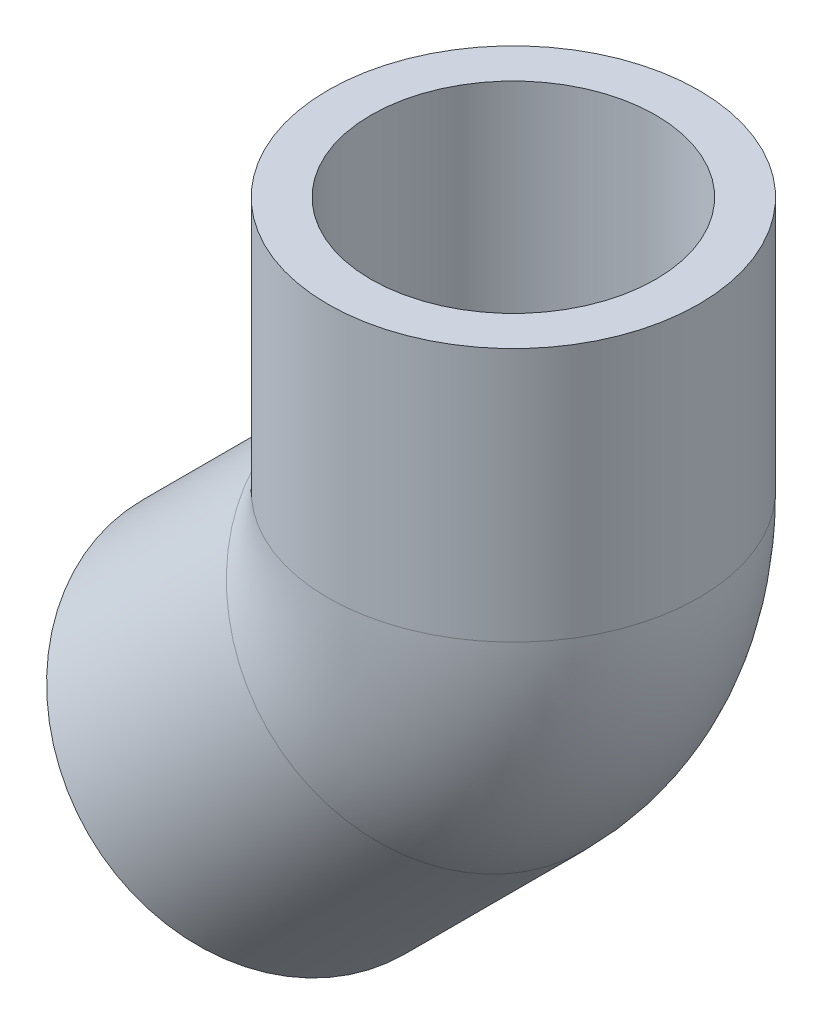
SolidWorks part; units mm, degrees
ref_plane "Front Plane" through (0, 0, 0) normal (0, 0, 1) x (1, 0, 0)
ref_plane "Top Plane" through (0, 0, 0) normal (0, 1, 0) x (1, 0, 0)
ref_plane "Right Plane" through (0, 0, 0) normal (1, 0, 0) x (0, 0, -1)
sketch "Sketch1" plane through (0, 0, 0) normal (0, 0, 1) x (1, 0, 0)
  line L0 (0, 0) -> (0, 25.4) construction
  line L1 (0, 0) -> (-17.9605, -17.9605) construction
  line L2 (-8.1361, -27.7849) -> (-27.7849, -8.1361) construction
  line L3 (10.668, 6.35) -> (-10.668, 6.35) construction
  line L4 (-13.8938, 25.4) -> (13.8938, 25.4) construction
  line L5 (3.0533, -12.0335) -> (-12.0335, 3.0533) construction
  point P6 (-17.9605, -17.9605)
  point P7 (-17.9605, -17.9605)
  point P11 (0, 6.35)
  point P15 (-4.4901, -4.4901)
  point P22 (0, 25.4)
  dimension "D1" = 19.05
  dimension "D2" = 45
  dimension "D3" = 21.336
  dimension "D4" = 6.35
  dimension "D6" = 27.7876
  dimension "D7" = 25.4
ref_plane "Plane1" through (0, 25.4, 0) normal (0, 1, 0) x (1, 0, 0)
sketch "Sketch2" plane through (0, 25.4, 0) normal (0, 1, 0) x (1, 0, 0)
  circle A0 centre (0, 0) radius 13.8938
  circle A1 centre (0, 0) radius 7.8994
  dimension "D1" = 27.7876
  dimension "D2" = 15.7988
sketch "Sketch3" plane through (0, 0, 0) normal (0, 0, 1) x (1, 0, 0)
  line L0 (-17.9605, -17.9605) -> (-4.4901, -4.4901)
  line L1 (0, 25.4) -> (0, 6.35)
  arc A0 (0, 6.35) -> (-4.4901, -4.4901) centre (-15.3303, 6.35) cw
sweep "Sweep1" add profiles "Sketch2" path "Sketch3"
sketch "Sketch5" plane through (0, 25.4, 0) normal (0, 1, 0) x (1, 0, 0)
  circle A0 centre (0, 0) radius 10.668
  dimension "D1" = 21.336
extrude "Cut-Extrude1" cut sketch "Sketch5" against normal blind 19.05
sketch "Sketch6" plane through (-17.9605, -17.9605, 0) normal (-0.7071, -0.7071, 0) x (0, 0, 1)
  circle A0 centre (0, 0) radius 10.668
  dimension "D1" = 21.336
extrude "Cut-Extrude2" cut sketch "Sketch6" against normal blind 19.05
